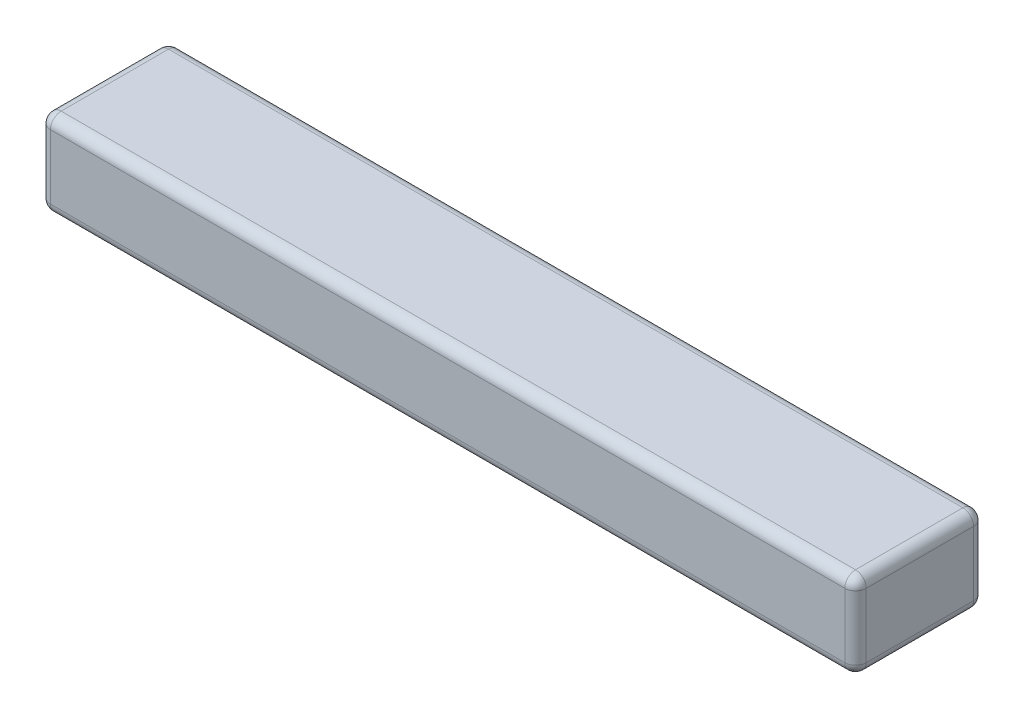
SolidWorks part; units mm, degrees
ref_plane "Front Plane" through (0, 0, 0) normal (0, 0, 1) x (1, 0, 0)
ref_plane "Top Plane" through (0, 0, 0) normal (0, 1, 0) x (1, 0, 0)
ref_plane "Right Plane" through (0, 0, 0) normal (1, 0, 0) x (0, 0, -1)
sketch "Sketch1" plane through (0, 0, 0) normal (1, 0, 0) x (0, 0, -1)
  line L1 (-30, -20) -> (30, -20)
  line L2 (-30, -20) -> (-30, 20)
  line L3 (-30, 20) -> (30, 20)
  line L4 (30, -20) -> (30, 20)
  line L5 (-30, -20) -> (30, 20) construction
  line L6 (-30, 20) -> (30, -20) construction
  point P0 (0, 0)
  dimension "D1" = 60
  dimension "D2" = 40
extrude "Boss-Extrude1" add sketch "Sketch1" along normal mid plane 380
fillet "Fillet1" radius 5 12 edges at (-190, -20, 0) (-190, 0, -30) (-190, 20, 0) (-190, 0, 30) (190, 0, -30) (190, 20, 0) (190, -20, 0) (190, 0, 30) (0, -20, -30) (0, 20, -30) (0, -20, 30) (0, 20, 30)
sketch "Sketch2" plane through (0, 0, 30) normal (0, 0, 1) x (1, 0, 0)
  line L0 (-100, 15) -> (-100, -15) construction
  line L1 (185, 15) -> (-185, 15) construction
  line L2 (-185, -15) -> (185, -15) construction
  line L3 (-190, -15) -> (-190, 15) construction
  line L4 (100, 15) -> (100, -15) construction
  line L5 (190, 15) -> (190, -15) construction
  dimension "D1" = 90
  dimension "D2" = 90
